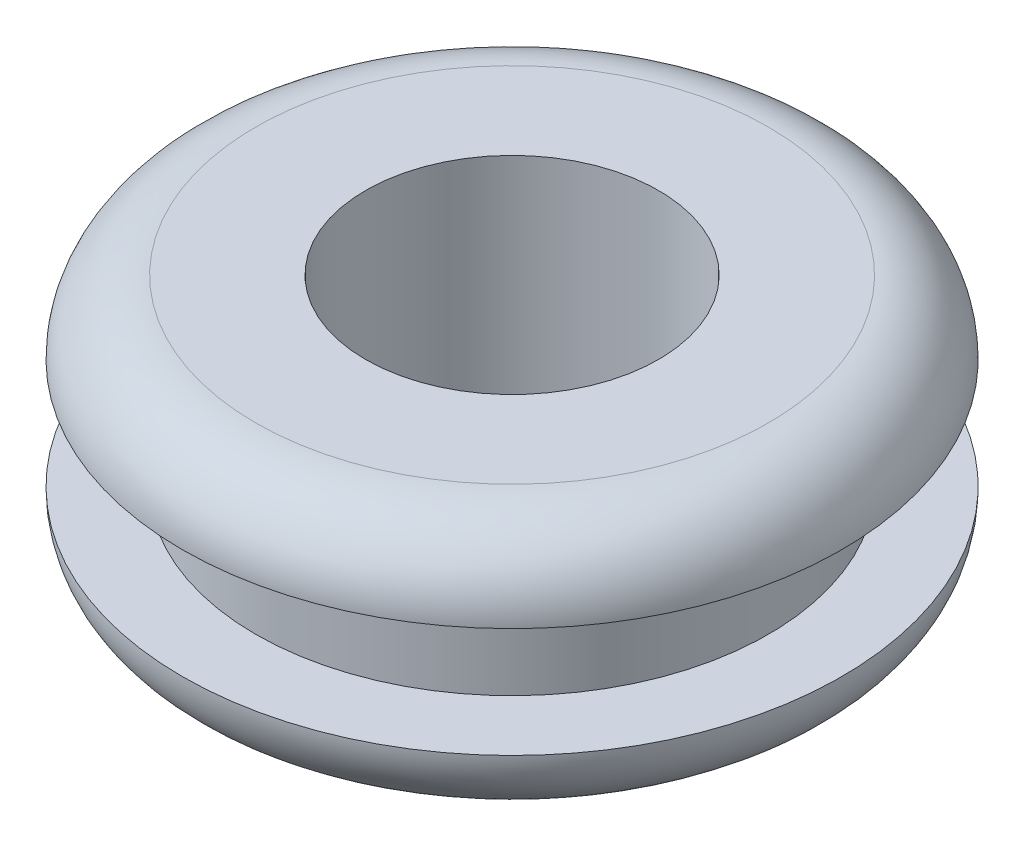
SolidWorks part; units mm, degrees
ref_plane "Front" through (0, 0, 0) normal (0, 0, 1) x (1, 0, 0)
ref_plane "Top" through (0, 0, 0) normal (0, 1, 0) x (1, 0, 0)
ref_plane "Right" through (0, 0, 0) normal (1, 0, 0) x (0, 0, -1)
sketch "Sketch1" plane through (0, 0, 0) normal (0, 0, 1) x (1, 0, 0)
  line L0 (-3.175, 0) -> (3.175, 0) construction
  line L1 (-5.5562, 0) -> (5.5562, 0) construction
  line L2 (0, 2.7781) -> (0, -2.7781) construction
  line L3 (7.1437, 2.7781) -> (-7.1437, 2.7781) construction
  line L4 (5.5562, 1.1906) -> (5.5562, -1.1906) construction
  dimension "ID" = 6.35
  dimension "for hole dia" = 11.1125
  dimension "oall ht" = 5.5562
  dimension "flange dia" = 14.2875
  dimension "material thick" = 2.3813
sketch "Sketch2" plane through (0, 0, 0) normal (0, 0, 1) x (1, 0, 0)
  line L0 (5.5562, 1.1906) -> (7.1437, 1.1906)
  line L1 (7.1437, 2.7781) -> (7.1438, -2.7781) construction
  line L2 (7.1437, 2.7781) -> (-7.1437, 2.7781) construction
  line L3 (3.175, 2.7781) -> (5.5562, 2.7781)
  line L4 (5.5562, 1.1906) -> (5.5562, -1.1906)
  line L5 (3.175, 2.7781) -> (3.175, -2.7781)
  line L6 (3.175, -2.7781) -> (5.5563, -2.7781)
  line L7 (7.1438, -1.1906) -> (5.5562, -1.1906)
  arc A0 (5.5562, 2.7781) -> (7.1437, 1.1906) centre (5.5562, 1.1906) cw
  arc A1 (5.5563, -2.7781) -> (7.1438, -1.1906) centre (5.5563, -1.1906) ccw
revolve "Revolve1" add sketch "Sketch2" angle 360 about L2
